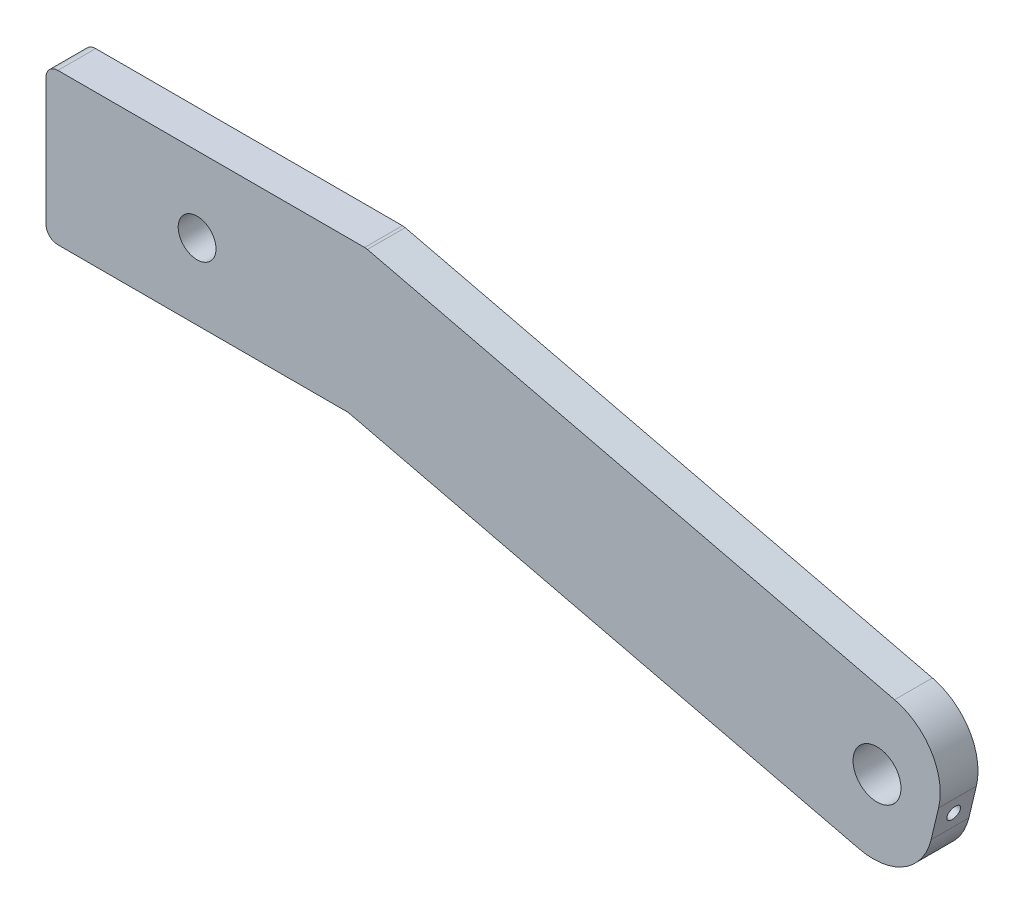
SolidWorks part; units mm, degrees
ref_plane "Front Plane" through (0, 0, 0) normal (0, 0, 1) x (1, 0, 0)
ref_plane "Top Plane" through (0, 0, 0) normal (0, 1, 0) x (1, 0, 0)
ref_plane "Right Plane" through (0, 0, 0) normal (1, 0, 0) x (0, 0, -1)
sketch "Sketch1" plane through (0, 0, 0) normal (0, 0, 1) x (1, 0, 0)
  line L0 (-12.7, 0) -> (-38.1, 0) construction
  line L2 (-38.1, -12.7) -> (-38.1, 12.7)
  line L5 (104.5604, -8.5999) -> (98.6396, -33.3001) construction
  line L6 (12.7, -12.7) -> (71.3084, -26.7487) construction
  line L19 (-12.7, 0) -> (0, 0) construction
  line L25 (15.7017, 12.7) -> (-38.1, 12.7)
  line L26 (12.7, -12.7) -> (-38.1, -12.7)
  line L27 (15.7017, 12.7) -> (74.6646, -1.4337) construction
  line L28 (15.7017, 12.7) -> (114.2849, -10.9309)
  line L29 (12.7, -12.7) -> (108.3641, -35.6312)
  line L30 (108.3641, -35.6312) -> (114.2849, -10.9309)
  circle A0 centre (-12.7, 0) radius 3.175
  circle A13 centre (101.6, -20.95) radius 4.025
  dimension "D4" = 6.35
  dimension "D7" = 10
  dimension "D8" = 25.4
  dimension "D10" = 25.4
  dimension "D5" = 101.6
  dimension "D6" = 20.95
  dimension "D9" = 8.05
  dimension "D2" = 12.7
  dimension "D3" = 12.7
  dimension "D13" = 25.4
extrude "Boss-Extrude1" add sketch "Sketch1" along normal blind 6.35
sketch "Sketch3" plane through (110.5529, -26.5001, 0) normal (0.9725, -0.2331, 0) x (0, 0, -1)
  line L0 (-6.35, 3.3102) -> (0, 3.3102) construction
  line L1 (-6.35, -9.3898) -> (-6.35, 16.0102) construction
  line L2 (0, -9.3898) -> (0, 16.0102) construction
  circle A0 centre (-3.175, 3.3102) radius 1.1303
  dimension "D1" = 2.2606
extrude "Cut-Extrude2" cut sketch "Sketch3" against normal up to next
fillet "Fillet4" radius 10 2 edges at (108.3641, -35.6312, 3.175) (114.2849, -10.9309, 3.175)
sketch "Sketch4" plane through (0, 0, 0) normal (0, 0, 1) x (1, 0, 0)
  line L0 (-25.4, -3.175) -> (-25.4, 3.175)
  line L1 (-25.4, -3.175) -> (-31.75, -3.175)
  line L2 (-25.4, 3.175) -> (-31.75, 3.175)
  line L3 (-31.75, -3.175) -> (-31.75, 3.175)
  line L4 (-25.4, -3.175) -> (-31.75, 3.175) construction
  line L5 (-25.4, 3.175) -> (-31.75, -3.175) construction
  line L6 (-38.1, 0) -> (0, 0) construction
  line L7 (0, 0) -> (68.6835, 0) construction
  line L8 (-4.7625, -3.175) -> (-4.7625, 3.175)
  line L9 (-4.7625, -3.175) -> (20.6375, -3.175)
  line L10 (-4.7625, 3.175) -> (20.6375, 3.175)
  line L11 (20.6375, -3.175) -> (20.6375, 3.175)
  line L12 (-4.7625, -3.175) -> (20.6375, 3.175) construction
  line L13 (-4.7625, 3.175) -> (20.6375, -3.175) construction
  line L14 (-38.1, 12.7) -> (-38.1, -12.7) construction
  line L15 (104.5604, -8.5999) -> (15.7017, 12.7) construction
  point P1 (-28.575, 0)
  point P3 (69.2018, -0.1242)
  point P13 (-12.7, 0)
  point P14 (7.9375, 0)
  dimension "D2" = 7.9375
  dimension "D1" = 6.35
  dimension "D3" = 12.7
  dimension "D4" = 25.4
  dimension "D5" = 6.35
extrude "Boss-Extrude2" add sketch "Sketch4" against normal blind 4.7625
fillet "Fillet3" radius 2 12 edges at (-38.1, -12.7, 3.175) (-38.1, 12.7, 3.175) (12.7, -12.7, 3.175) (15.7017, 12.7, 3.175) (20.6375, -3.175, -2.3813) (20.6375, 3.175, -2.3813) (-4.7625, 3.175, -2.3813) (-4.7625, -3.175, -2.3813) (-31.75, 3.175, -2.3813) (-31.75, -3.175, -2.3813) (-25.4, -3.175, -2.3813) (-25.4, 3.175, -2.3813)
